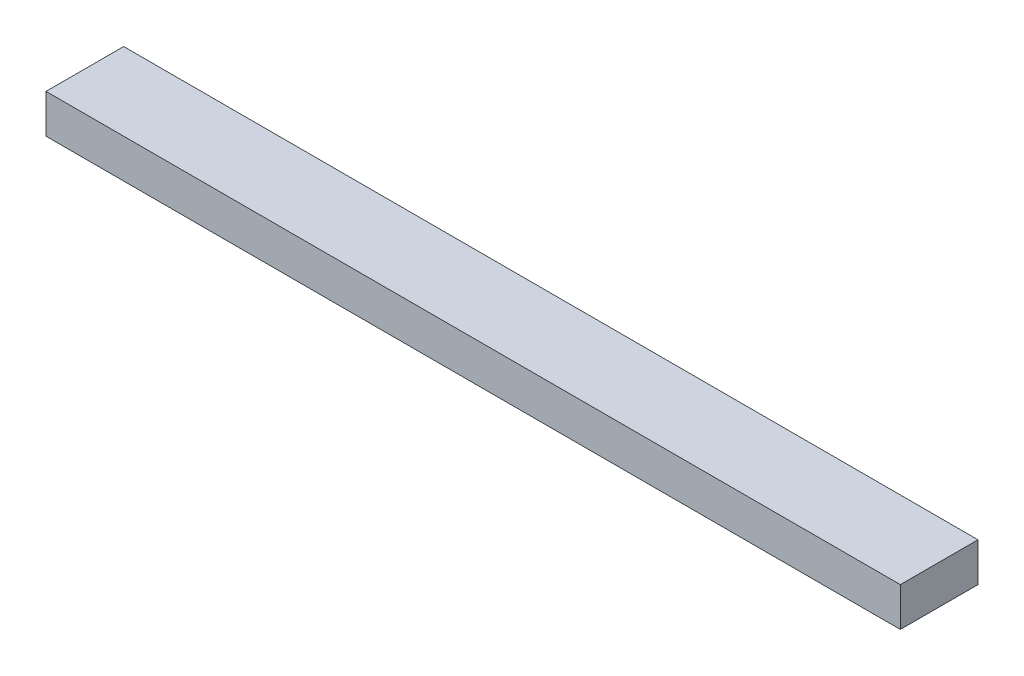
SolidWorks part; units mm, degrees
ref_plane "Front Plane" through (0, 0, 0) normal (0, 0, 1) x (1, 0, 0)
ref_plane "Top Plane" through (0, 0, 0) normal (0, 1, 0) x (1, 0, 0)
ref_plane "Right Plane" through (0, 0, 0) normal (1, 0, 0) x (0, 0, -1)
sketch "Sketch1" plane through (0, 0, 0) normal (0, 1, 0) x (1, 0, 0)
  line L1 (-55, -5) -> (55, -5)
  line L2 (-55, -5) -> (-55, 5)
  line L3 (-55, 5) -> (55, 5)
  line L4 (55, -5) -> (55, 5)
  line L5 (-55, -5) -> (55, 5) construction
  line L6 (-55, 5) -> (55, -5) construction
  point P0 (0, 0)
  dimension "D1" = 110
  dimension "D2" = 10
extrude "Boss-Extrude1" add sketch "Sketch1" along normal blind 5
sketch "Sketch2" plane through (0, 5, 0) normal (0, 1, 0) x (1, 0, 0)
  line L0 (55, 5) -> (-55, 5) construction
  line L1 (-50, -5) -> (50, -5)
  line L2 (-50, -5) -> (-50, 5) construction
  line L3 (-50, 5) -> (50, 5)
  line L4 (50, -5) -> (50, 5)
  line L5 (-50, -5) -> (50, 5) construction
  line L6 (-50, 5) -> (50, -5) construction
  point P0 (0, 0)
  dimension "D1" = 100
sketch "Sketch3" plane through (0, 5, 0) normal (0, 1, 0) x (1, 0, 0)
  line L0 (-55, 5) -> (-55, -5) construction
  line L1 (-55, -1.9317) -> (-50, -1.9317)
  line L2 (-55, -1.9317) -> (-55, 2.0683)
  line L3 (-55, 2.0683) -> (-50, 2.0683)
  line L4 (-50, -1.9317) -> (-50, 2.0683)
  line L5 (0, 12.1451) -> (0, -20.2163) construction
  line L6 (55, -1.9317) -> (50, -1.9317)
  line L7 (55, -1.9317) -> (55, 2.0683)
  line L8 (55, 2.0683) -> (50, 2.0683)
  line L9 (50, -1.9317) -> (50, 2.0683)
  dimension "D1" = 4
  dimension "D2" = 5
